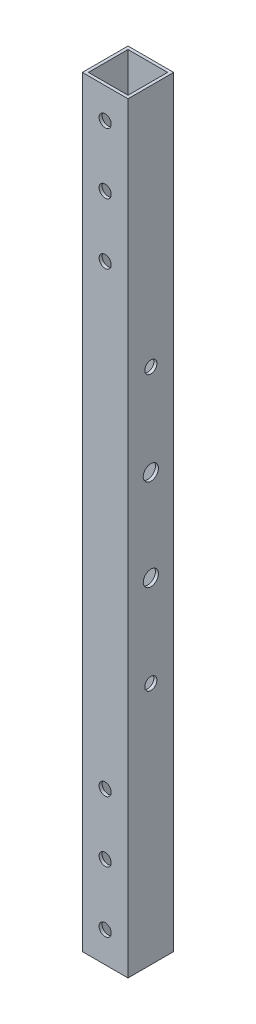
SolidWorks part; units mm, degrees
material "6061 合金"
ref_plane "Front" through (0, 0, 0) normal (0, 0, 1) x (1, 0, 0)
ref_plane "Top" through (0, 0, 0) normal (0, 1, 0) x (1, 0, 0)
ref_plane "Right" through (0, 0, 0) normal (1, 0, 0) x (0, 0, -1)
sketch "草图1" plane through (0, 0, 0) normal (0, 1, 0) x (1, 0, 0)
  line L1 (-7.5, -7.5) -> (7.5, -7.5)
  line L2 (-7.5, -7.5) -> (-7.5, 7.5)
  line L3 (-7.5, 7.5) -> (7.5, 7.5)
  line L4 (7.5, -7.5) -> (7.5, 7.5)
  line L5 (-7.5, -7.5) -> (7.5, 7.5) construction
  line L6 (-7.5, 7.5) -> (7.5, -7.5) construction
  line L7 (-6.5, -6.5) -> (6.5, -6.5)
  line L8 (-6.5, -6.5) -> (-6.5, 6.5)
  line L9 (-6.5, 6.5) -> (6.5, 6.5)
  line L10 (6.5, -6.5) -> (6.5, 6.5)
  line L11 (-6.5, -6.5) -> (6.5, 6.5) construction
  line L12 (-6.5, 6.5) -> (6.5, -6.5) construction
  point P0 (0, 0)
  point P5 (0, 0)
  dimension "D1" = 15
  dimension "D2" = 15
  dimension "D3" = 1
  dimension "D4" = 1
extrude "凸台-拉伸1" add sketch "草图1" along normal blind 250
sketch "草图3" plane through (0, 0, 7.5) normal (0, 0, 1) x (1, 0, 0)
  line L0 (0, 50) -> (0, -49950) construction
  line L1 (-7.5, 250) -> (7.5, 250) construction
  line L2 (5, 125) -> (-49995, 125) construction
  line L3 (7.5, 250) -> (7.5, 0) construction
  circle A0 centre (0, 240) radius 2
  circle A1 centre (0, 220) radius 2
  circle A2 centre (0, 30) radius 2
  circle A3 centre (0, 10) radius 2
  circle A4 centre (0, 200) radius 2
  circle A5 centre (0, 50) radius 2
  point P4 (0, 250)
  point P13 (7.5, 125)
  dimension "D1" = 4
  dimension "D2" = 4
  dimension "D5" = 4
  dimension "D3" = 20
  dimension "D4" = 10
  dimension "D6" = 20
extrude "切除-拉伸2" cut sketch "草图3" against normal through all
sketch "草图5" plane through (7.5, 0, 0) normal (1, 0, 0) x (0, 0, -1)
  line L0 (-5, 125) -> (49995, 125) construction
  line L1 (-7.5, 250) -> (-7.5, 0) construction
  line L2 (7.5, 250) -> (7.5, 0) construction
  line L3 (0, 0) -> (0, 50000) construction
  circle A1 centre (0, 140) radius 2.5
  circle A2 centre (0, 110) radius 2.5
  circle A3 centre (0, 170) radius 2
  circle A4 centre (0, 80) radius 2
  point P4 (-7.5, 125)
  point P7 (7.5, 125)
  dimension "D1" = 5
  dimension "D3" = 4
  dimension "D2" = 30
  dimension "D4" = 90
extrude "切除-拉伸4" cut sketch "草图5" against normal through all
equation "\"3。3\"=3.01309"
